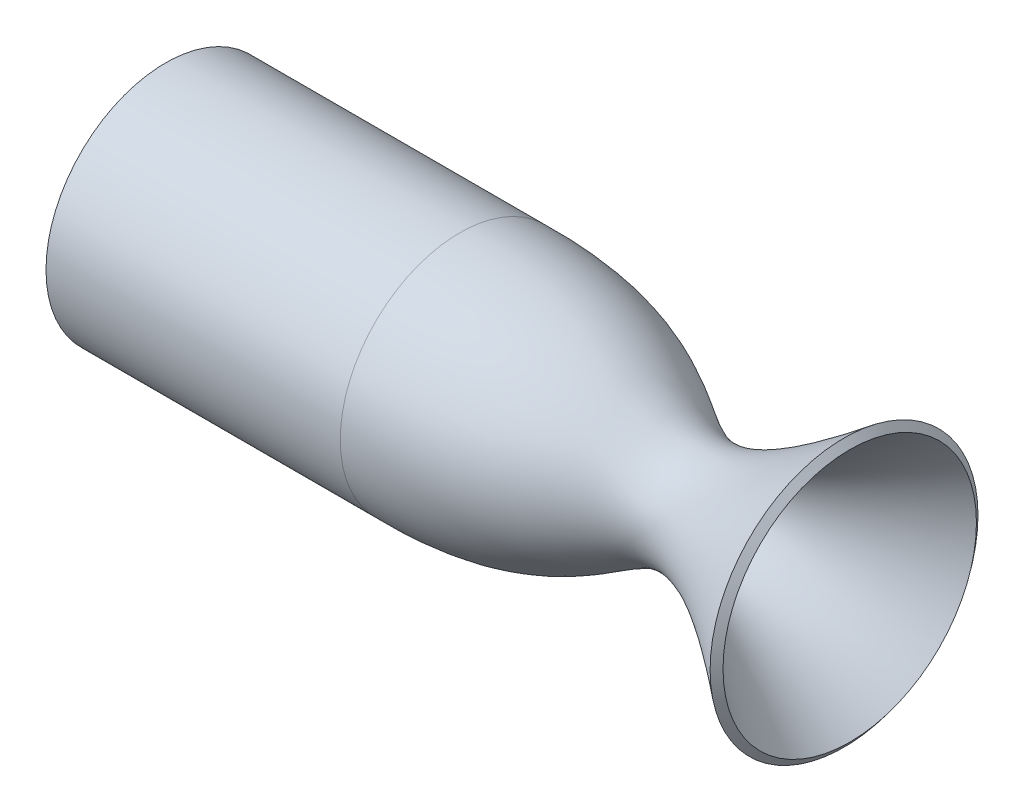
SolidWorks part; units mm, degrees
ref_plane "Front Plane" through (0, 0, 0) normal (0, 0, 1) x (1, 0, 0)
ref_plane "Top Plane" through (0, 0, 0) normal (0, 1, 0) x (1, 0, 0)
ref_plane "Right Plane" through (0, 0, 0) normal (1, 0, 0) x (0, 0, -1)
sketch "Sketch2" plane through (0, 0, 0) normal (0, 0, 1) x (1, 0, 0)
  line L0 (-140, 0) -> (231.919, 0) construction
  line L1 (-140, 65) -> (19.9542, 65)
  line L2 (-140, 60) -> (19.9542, 60)
  line L3 (-140, 65) -> (-140, 60)
  line L4 (228.8309, 72.8135) -> (231.919, 68.8811)
  arc A0 (19.9542, 60) -> (20.0454, 60.0008) centre (19.9542, 65) ccw
  arc A1 (19.9542, 65) -> (19.9542, 65) centre (19.9542, 65) ccw
  spline S0 degree 3 poles (20.0454, 60.0008) (155.1338, 62.4645) (107.1587, -29.092) (231.919, 68.8811) knots 0.000112 0.000112 0.000112 0.000112 1 1 1 1
  spline S1 degree 1 poles (19.9542, 65) (228.8309, 72.8135) knots 0 0 1 1 construction
  spline S2 degree 3 poles (19.9542, 65) (21.016, 65.0194) (23.1558, 65.0471) (27.3086, 65.0564) (32.3532, 64.9847) (38.1529, 64.7711) (45.5677, 64.3249) (54.2551, 63.4798) (63.8139, 62.0562) (72.567, 60.2739) (83.2429, 57.4888) (94.8674, 53.3738) (106.5183, 47.8745) (116.3228, 42.2985) (124.736, 37.1417) (132.1972, 32.8764) (139.1182, 29.887) (146.0093, 28.3695) (153.7244, 28.4982) (163.1638, 30.7745) (172.9397, 34.9683) (182.1185, 39.947) (189.7351, 44.5463) (198.1395, 50.0633) (205.8471, 55.4678) (212.4658, 60.3012) (217.6617, 64.186) (222.1979, 67.6504) (225.9391, 70.5491) (227.8739, 72.0619) (228.8309, 72.8135) knots 0.000112 0.000112 0.000112 0.000112 0.007924 0.015735 0.031358 0.046982 0.062605 0.093851 0.125098 0.156344 0.187591 0.250084 0.312577 0.37507 0.437563 0.500056 0.562549 0.625042 0.687535 0.750028 0.812521 0.843767 0.875014 0.90626 0.937507 0.95313 0.968753 0.984377 0.992188 1 1 1 1
  dimension "D2" = 5
  dimension "D1" = 60
  dimension "D3" = 68.8811
  dimension "D4" = 5
revolve "Revolve1" add sketch "Sketch2" angle 360 about L0
